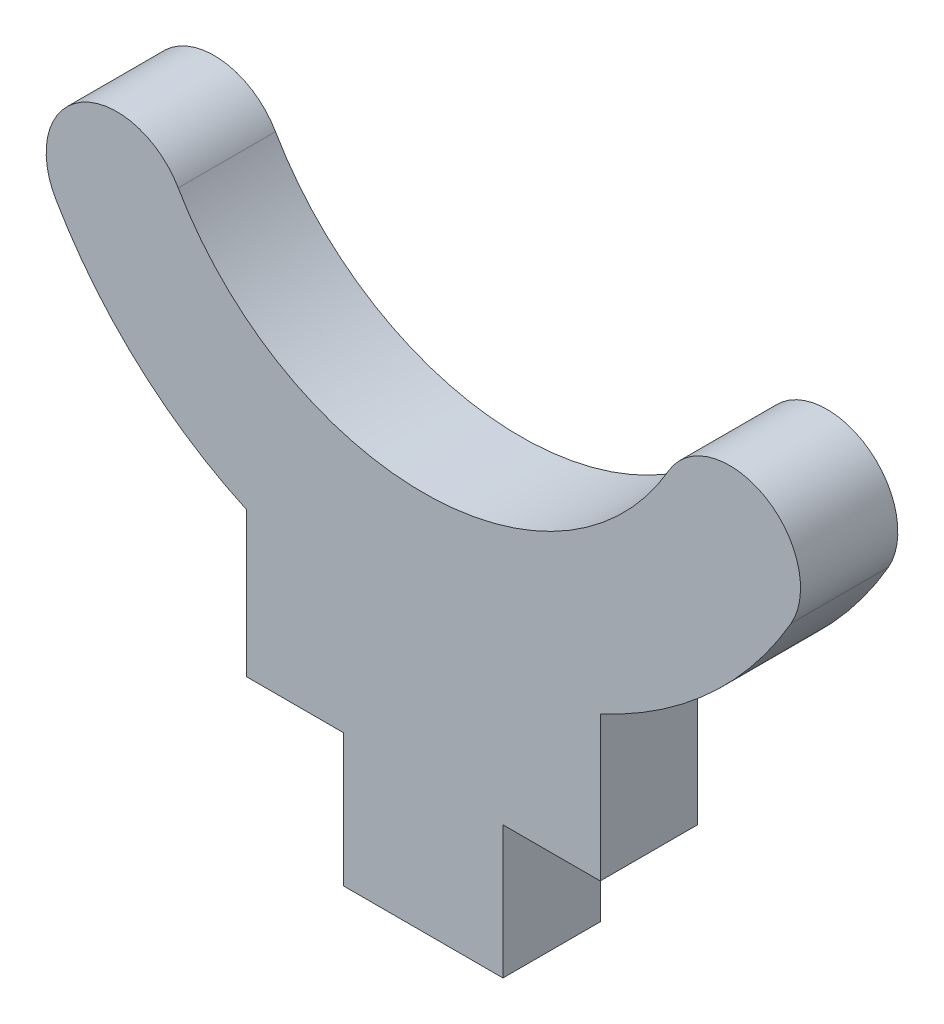
SolidWorks part; units mm, degrees
material "ﾁｰｸ材"
ref_plane "正面" through (0, 0, 0) normal (0, 0, 1) x (1, 0, 0)
ref_plane "平面" through (0, 0, 0) normal (0, 1, 0) x (1, 0, 0)
ref_plane "右側面" through (0, 0, 0) normal (1, 0, 0) x (0, 0, -1)
sketch "ｽｹｯﾁ1" plane through (0, 0, 0) normal (0, 0, 1) x (1, 0, 0)
  line L8 (-10, 15.6826) -> (-10, 0)
  line L9 (-10, 0) -> (10, 0)
  line L10 (10, 0) -> (10, 15.6826)
  arc A0 (-13.8564, 29.5) -> (13.8564, 29.5) centre (0, 37.5) ccw
  arc A1 (13.8564, 29.5) -> (20.7846, 25.5) centre (17.3205, 27.5) cw
  arc A2 (20.7846, 25.5) -> (10, 15.6826) centre (0, 37.5) cw
  arc A3 (-20.7846, 25.5) -> (-13.8564, 29.5) centre (-17.3205, 27.5) cw
  arc A4 (-10, 15.6826) -> (-20.7846, 25.5) centre (0, 37.5) cw
  point P9 (0, 0)
  point P13 (9.1287, -24.4077)
  point P15 (0, 0)
  dimension "D1" = 16
  dimension "D5" = 24
  dimension "D2" = 120
  dimension "D3" = 20
  dimension "D4" = 37.5
extrude "ﾎﾞｽ - 押し出し1" add sketch "ｽｹｯﾁ1" along normal blind 5.5
sketch "ｽｹｯﾁ2" plane through (0, 0, 5.5) normal (0, 0, 1) x (1, 0, 0)
  line L1 (10, 0) -> (4.5, 0)
  line L2 (10, 0) -> (10, 7.5)
  line L3 (10, 7.5) -> (4.5, 7.5)
  line L4 (4.5, 0) -> (4.5, 7.5)
  line L5 (-10, 0) -> (-4.5, 0)
  line L6 (-10, 0) -> (-10, 7.5)
  line L7 (-10, 7.5) -> (-4.5, 7.5)
  line L8 (-4.5, 0) -> (-4.5, 7.5)
  dimension "D1" = 7.5
  dimension "D2" = 5.5
  dimension "D3" = 5.5
extrude "ｶｯﾄ - 押し出し1" cut sketch "ｽｹｯﾁ2" against normal through all
